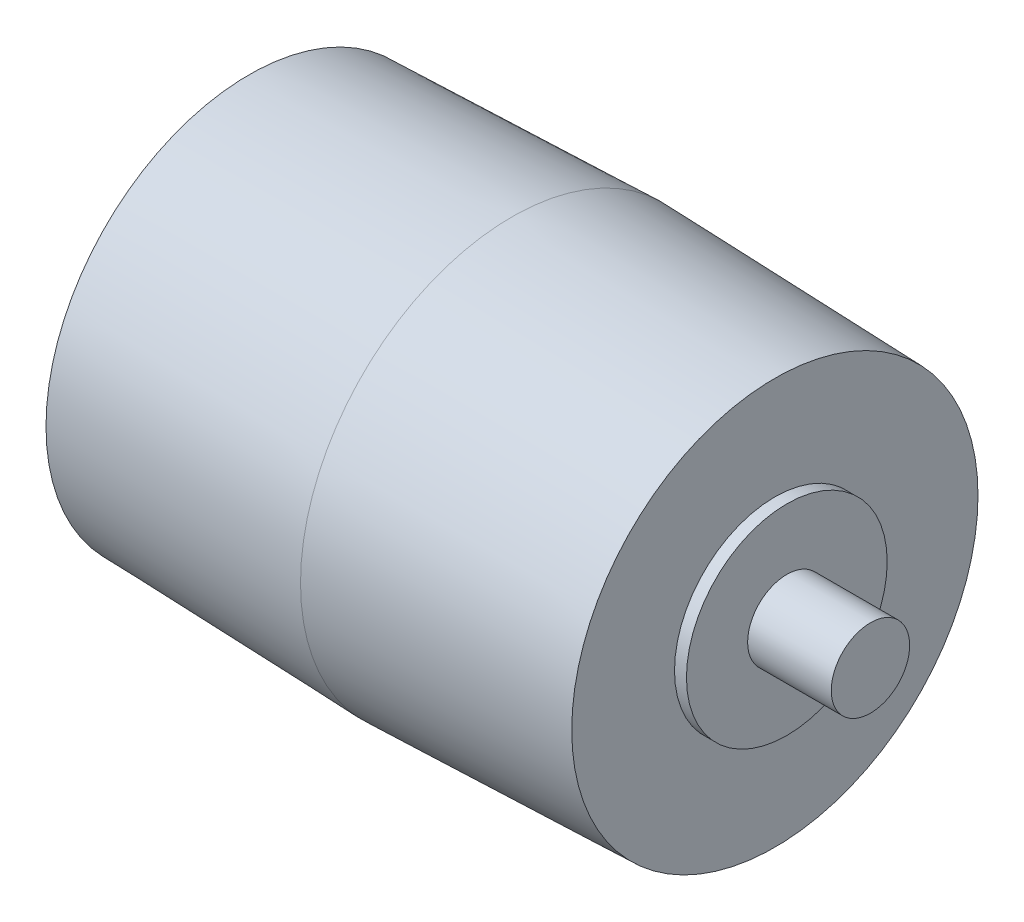
SolidWorks part; units mm, degrees
ref_plane "Front Plane" through (0, 0, 0) normal (0, 0, 1) x (1, 0, 0)
ref_plane "Top Plane" through (0, 0, 0) normal (0, 1, 0) x (1, 0, 0)
ref_plane "Right Plane" through (0, 0, 0) normal (1, 0, 0) x (0, 0, -1)
sketch "Sketch1" plane through (0, 0, 0) normal (0, 0, 1) x (1, 0, 0)
  line L0 (-9.525, 0) -> (-9.525, 1.0414)
  line L1 (-9.525, 1.0414) -> (-7.3025, 1.0414)
  line L2 (-7.3025, 1.0414) -> (-7.3025, 2.667)
  line L3 (-7.3025, 2.667) -> (-6.985, 2.667)
  line L4 (-6.985, 2.667) -> (-6.985, 5.3975)
  line L5 (-6.985, 5.3975) -> (0, 5.6197)
  line L6 (0, 5.6197) -> (0, 0) construction
  line L7 (9.525, 0) -> (-9.525, 0) construction
  line L8 (6.985, 5.3975) -> (0, 5.6197)
  line L9 (6.985, 2.667) -> (6.985, 5.3975)
  line L10 (7.3025, 2.667) -> (6.985, 2.667)
  line L11 (7.3025, 1.0414) -> (7.3025, 2.667)
  line L12 (9.525, 1.0414) -> (7.3025, 1.0414)
  line L13 (9.525, 0) -> (9.525, 1.0414)
  line L14 (-9.525, 0) -> (9.525, 0)
  dimension "D1" = 19.05
  dimension "D2" = 2.0828
  dimension "D3" = 14.605
  dimension "D4" = 13.97
  dimension "D5" = 11.2395
  dimension "D6" = 10.795
  dimension "D7" = 5.334
revolve "Revolve1" add sketch "Sketch1" angle 360 about L14
